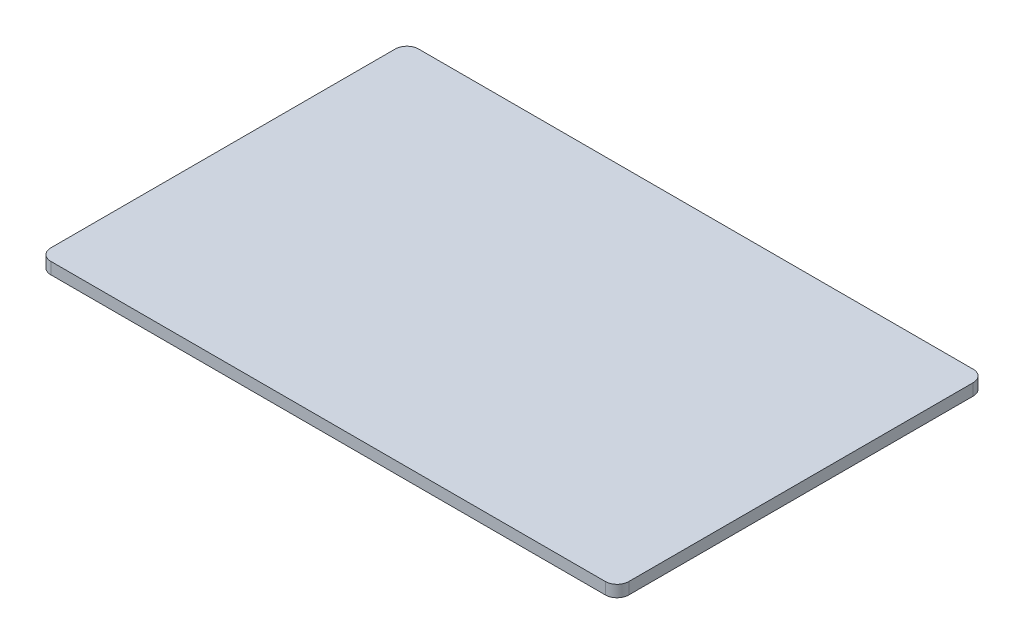
SolidWorks part; units mm, degrees
ref_plane "Front Plane" through (0, 0, 0) normal (0, 0, 1) x (1, 0, 0)
ref_plane "Top Plane" through (0, 0, 0) normal (0, 1, 0) x (1, 0, 0)
ref_plane "Right Plane" through (0, 0, 0) normal (1, 0, 0) x (0, 0, -1)
sketch "Sketch1" plane through (0, 0, 0) normal (0, 1, 0) x (1, 0, 0)
  line L1 (-49.5, 31.5) -> (49.5, 31.5)
  line L2 (-49.5, 31.5) -> (-49.5, -31.5)
  line L3 (-49.5, -31.5) -> (49.5, -31.5)
  line L4 (49.5, 31.5) -> (49.5, -31.5)
  point P4 (49.5, 0)
  point P6 (0, 31.5)
  dimension "D1" = 63
  dimension "D2" = 99
extrude "Boss-Extrude1" add sketch "Sketch1" along normal blind 2
fillet "Fillet1" radius 2 4 edges at (-49.5, 1, -31.5) (49.5, 1, -31.5) (49.5, 1, 31.5) (-49.5, 1, 31.5)
